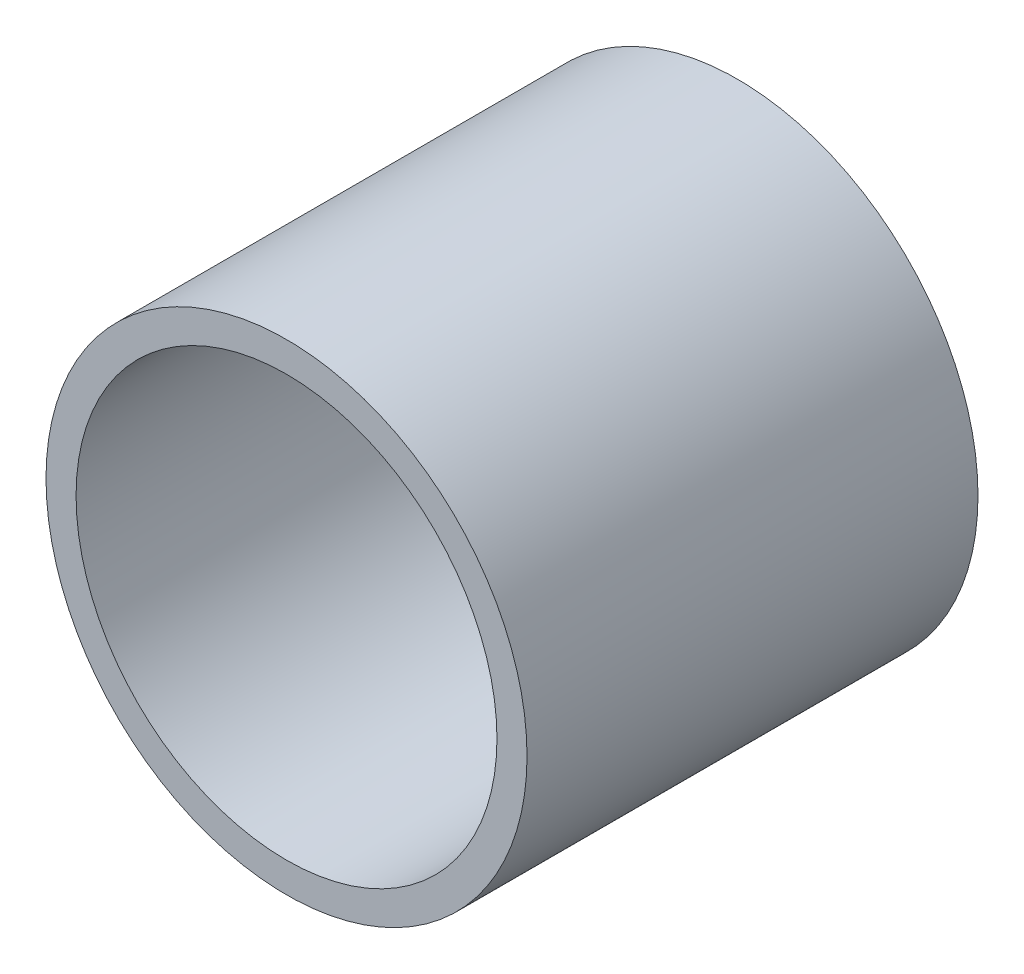
SolidWorks part; units mm, degrees
ref_plane "Front" through (0, 0, 0) normal (0, 0, 1) x (1, 0, 0)
ref_plane "Top" through (0, 0, 0) normal (0, 1, 0) x (1, 0, 0)
ref_plane "Right" through (0, 0, 0) normal (1, 0, 0) x (0, 0, -1)
sketch "Sketch2" plane through (0, 0, 0) normal (0, 0, 1) x (1, 0, 0)
  circle A0 centre (0, 0) radius 24
  circle A1 centre (0, 0) radius 21
  dimension "D1" = 42
  dimension "D2" = 48
extrude "Boss-Extrude1" add sketch "Sketch2" along normal blind 45
